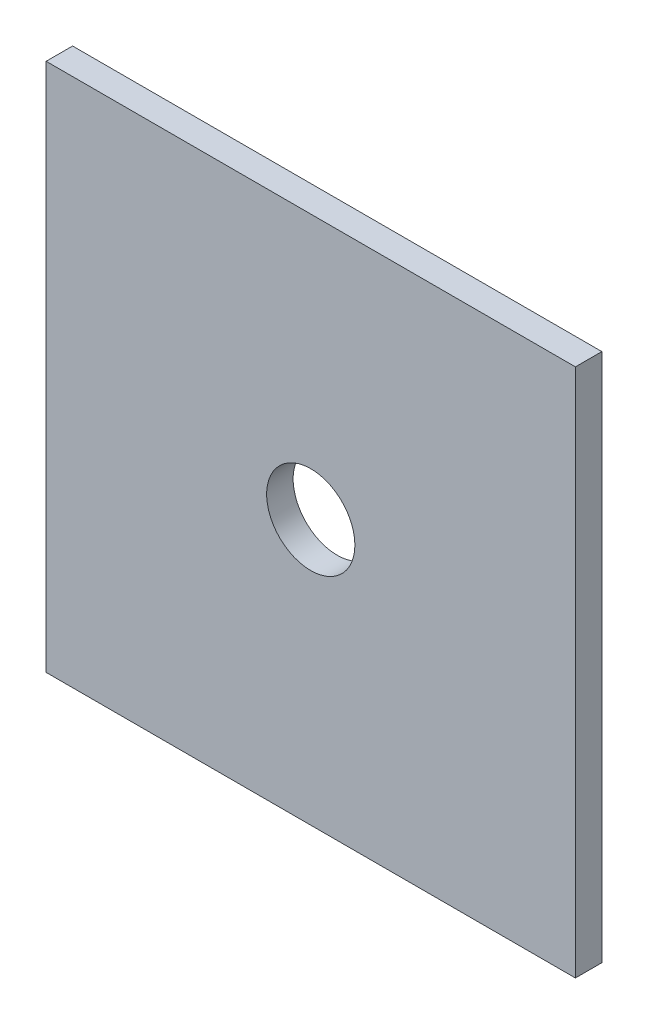
SolidWorks part; units mm, degrees
ref_plane "正面" through (0, 0, 0) normal (0, 0, 1) x (1, 0, 0)
ref_plane "平面" through (0, 0, 0) normal (0, 1, 0) x (1, 0, 0)
ref_plane "右側面" through (0, 0, 0) normal (1, 0, 0) x (0, 0, -1)
sketch "ｽｹｯﾁ1" plane through (0, 0, 0) normal (0, 0, 1) x (1, 0, 0)
  line L0 (150, 0) -> (-150, 0) construction
  line L1 (-150, 150) -> (150, 150)
  line L2 (-150, 150) -> (-150, -150)
  line L3 (-150, -150) -> (150, -150)
  line L4 (150, 150) -> (150, -150)
  circle A0 centre (0, 0) radius 25
  point P8 (0, 0)
  dimension "D3" = 50
  dimension "D1" = 300
  dimension "D2" = 300
extrude "ﾎﾞｽ - 押し出し1" add sketch "ｽｹｯﾁ1" along normal blind 15
